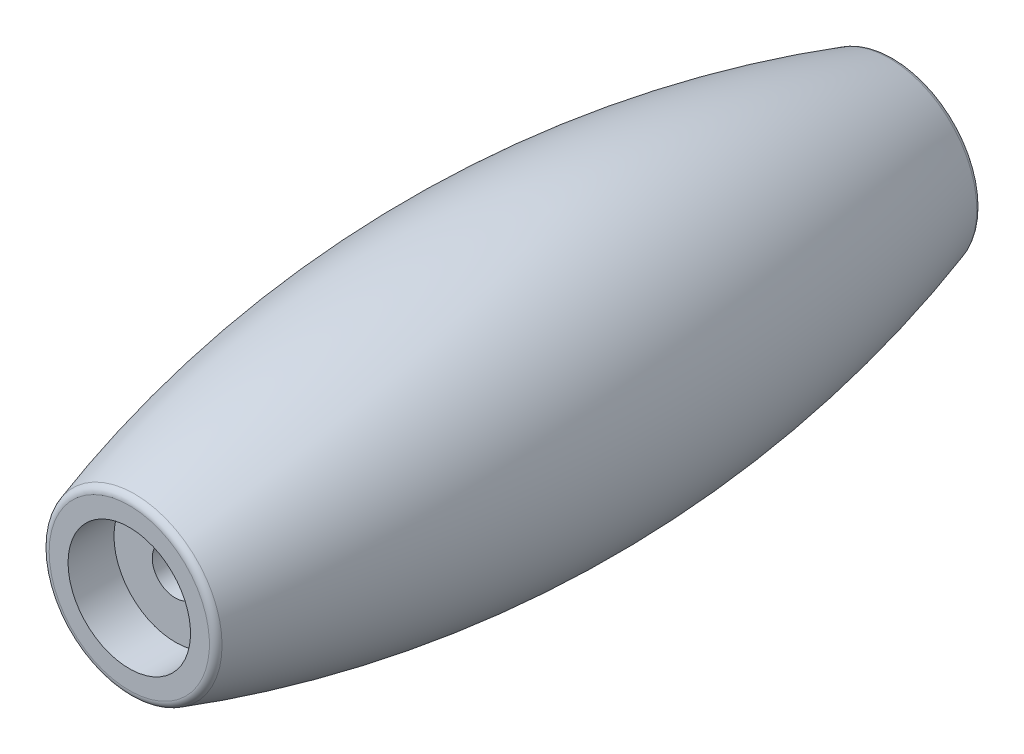
SolidWorks part; units mm, degrees
material "Silicon Rubber"
ref_plane "Front Plane" through (0, 0, 0) normal (0, 0, 1) x (1, 0, 0)
ref_plane "Top Plane" through (0, 0, 0) normal (0, 1, 0) x (1, 0, 0)
ref_plane "Right Plane" through (0, 0, 0) normal (1, 0, 0) x (0, 0, -1)
sketch "Sketch1" plane through (0, 0, 0) normal (0, 1, 0) x (1, 0, 0)
  line L0 (0, 10.7187) -> (0, -33.2813)
  line L1 (4, 13.7187) -> (5.6, 13.7187)
  line L2 (4, -36.2813) -> (5.6, -36.2813)
  line L3 (4, 13.7187) -> (4, 10.7187)
  line L4 (4, 10.7187) -> (0, 10.7187)
  line L5 (4, -36.2813) -> (4, -33.2813)
  line L6 (4, -33.2813) -> (0, -33.2813)
  arc A0 (5.6, 13.7187) -> (5.6, -36.2813) centre (-72.5782, -11.2813) cw
  point P6 (9.5, -11.2813)
  dimension "D1" = 44
  dimension "D2" = 9.5
  dimension "D4" = 4
  dimension "D5" = 3
revolve "Revolve1" add sketch "Sketch1" angle 360 about L0
sketch "Sketch2" plane through (0, 0, 36.2813) normal (0, 0, 1) x (1, 0, 0)
  circle A0 centre (0, 0) radius 1.5
  dimension "D1" = 3
extrude "Cut-Extrude1" cut sketch "Sketch2" against normal through all
fillet "Fillet1" radius 0.5 2 edges at (-5.6, 0, 36.2813) (-5.6, 0, -13.7187)
